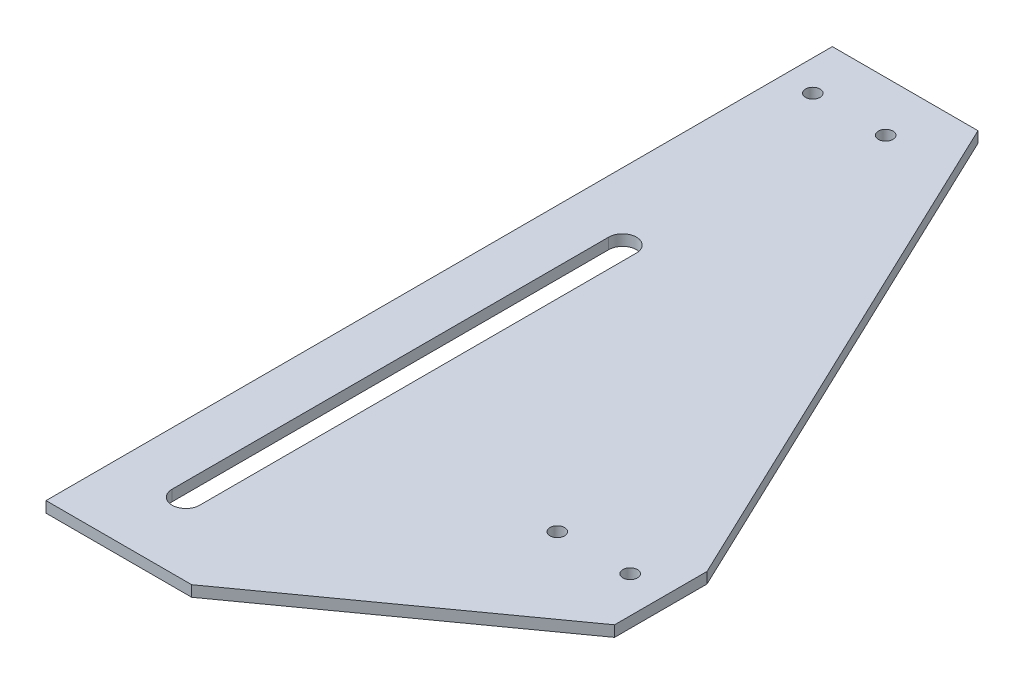
SolidWorks part; units mm, degrees
material "WhitePLA"
ref_plane "Front Plane" through (0, 0, 0) normal (0, 0, 1) x (1, 0, 0)
ref_plane "Top Plane" through (0, 0, 0) normal (0, 1, 0) x (1, 0, 0)
ref_plane "Right Plane" through (0, 0, 0) normal (1, 0, 0) x (0, 0, -1)
sketch "Sketch1" plane through (0, 0, 0) normal (0, 1, 0) x (1, 0, 0)
  line L0 (-33.8006, 83.7008) -> (0, 12.7)
  line L1 (-42.7, -14.2595) -> (-42.7, 45.7008)
  line L2 (-46.5, -14.2595) -> (-46.5, 45.7008)
  line L21 (-33.8006, 83.7008) -> (-53.8006, 83.7008)
  line L22 (-53.8006, 83.7008) -> (-53.8006, -24.2595)
  line L23 (0, 12.7) -> (0, 0)
  line L27 (-44.6, -14.2595) -> (-44.6, -24.2595)
  line L28 (-53.8006, -24.2595) -> (-33.8006, -24.2595)
  line L29 (-33.8006, -24.2595) -> (0, 0)
  circle A14 centre (-39.6, 76.82) radius 1
  circle A15 centre (-49.6, 76.82) radius 1
  arc A16 (-42.7, 45.7008) -> (-46.5, 45.7008) centre (-44.6, 45.7008) ccw
  circle A18 centre (-5, 7.14) radius 1
  circle A19 centre (-15, 7.14) radius 1
  arc A21 (-46.5, -14.2595) -> (-42.7, -14.2595) centre (-44.6, -14.2595) ccw
  dimension "D1" = 10
  dimension "D2" = 2
  dimension "D3" = 1.9
  dimension "D4" = 5
  dimension "D5" = 15
  dimension "D6" = 33.8006
  dimension "D7" = 39.6
  dimension "D8" = 44.6
  dimension "D9" = 7.14
  dimension "D10" = 49.6
  dimension "D11" = 53.8006
  dimension "D12" = 12.7
  dimension "D14" = 76.82
  dimension "D15" = 83.7008
  dimension "D16" = 14.2595
  dimension "D17" = 38
extrude "Boss-Extrude1" add sketch "Sketch1" along normal blind 1.5
